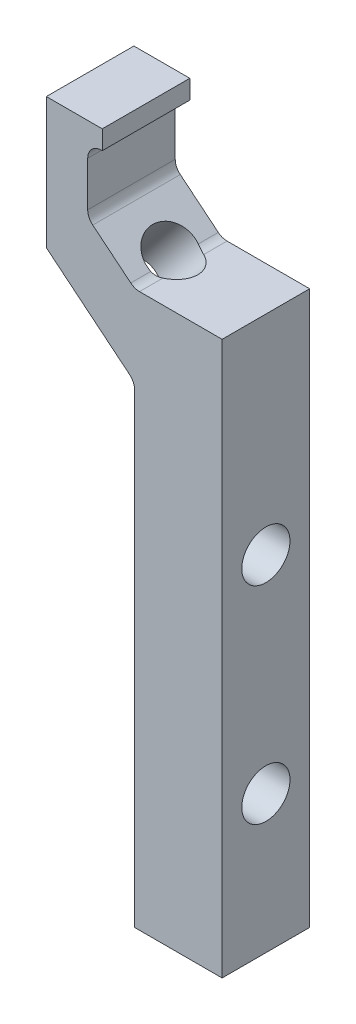
SolidWorks part; units mm, degrees
ref_plane "Front Plane" through (0, 0, 0) normal (0, 0, 1) x (1, 0, 0)
ref_plane "Top Plane" through (0, 0, 0) normal (0, 1, 0) x (1, 0, 0)
ref_plane "Right Plane" through (0, 0, 0) normal (1, 0, 0) x (0, 0, -1)
sketch "Sketch1" plane through (0, 0, 0) normal (0, 0, 1) x (1, 0, 0)
  line L4 (-312.7, 0) -> (-300, 0)
  line L12 (-312.7, 60.3) -> (-312.7, 0)
  line L24 (-312.7, 63.3) -> (-312.7, 60.3)
  line L25 (-300, 0) -> (-300, 80.2494)
  line L26 (-317.3886, 98) -> (-318.5, 98)
  line L28 (-317.1701, 83.9108) -> (-313.2528, 80.7022)
  line L29 (-312.7, 67.5688) -> (-312.7, 63.3)
  line L30 (-317.3886, 98) -> (-317.3886, 96.25)
  line L32 (-317.3886, 96.25) -> (-317.3886, 95.25)
  line L34 (-318.5, 98) -> (-325.5, 98)
  line L35 (-325.5, 98) -> (-325.5, 85)
  line L36 (-325.5, 85) -> (-325.5, 82)
  line L39 (-311.9855, 80.2494) -> (-300, 80.2494)
  line L41 (-319.5, 93.25) -> (-319.5, 86.7662)
  line L42 (-318.5, 85) -> (-317.1701, 83.9108)
  line L43 (-318.5, 85) -> (-318.7673, 85.2189)
  line L44 (-317.5, 95.25) -> (-317.3886, 95.25)
  line L45 (-325.5, 82) -> (-325.5, 79)
  line L46 (-325.5, 79) -> (-313.4327, 69.1161)
  arc A4 (-317.5, 95.25) -> (-319.5, 93.25) centre (-317.5, 93.25) ccw
  arc A5 (-311.9855, 80.2494) -> (-313.2528, 80.7022) centre (-311.9855, 82.2494) cw
  arc A6 (-318.7673, 85.2189) -> (-319.5, 86.7662) centre (-317.5, 86.7662) cw
  arc A7 (-312.7, 67.5688) -> (-313.4327, 69.1161) centre (-314.7, 67.5688) ccw
  dimension "D1" = 2
  dimension "D2" = 2
  dimension "D3" = 2
extrude "Boss-Extrude1" add sketch "Sketch1" along normal blind 12.7
sketch "Sketch2" plane through (-312.7, 0, 0) normal (-1, 0, 0) x (0, 0, 1)
  line L0 (6.35, 0) -> (6.35, 20)
  line L1 (12.7, 0) -> (0, 0) construction
  line L2 (6.35, 20) -> (6.35, 50)
sketch "Sketch6" plane through (-312.7, 0, 0) normal (-1, 0, 0) x (0, 0, 1)
  circle A0 centre (6.35, 50) radius 3.5
  circle A1 centre (6.35, 20) radius 3.5
extrude "Cut-Extrude1" cut sketch "Sketch6" against normal through all and the other way through all
sketch "Sketch8" plane through (-91.9656, -112.2807, 0) normal (-0.6336, -0.7736, 0) x (0.7736, -0.6336, 0)
  circle A0 centre (-294.0726, 6.35) radius 3.5
extrude "Cut-Extrude2" cut sketch "Sketch8" against normal through all
